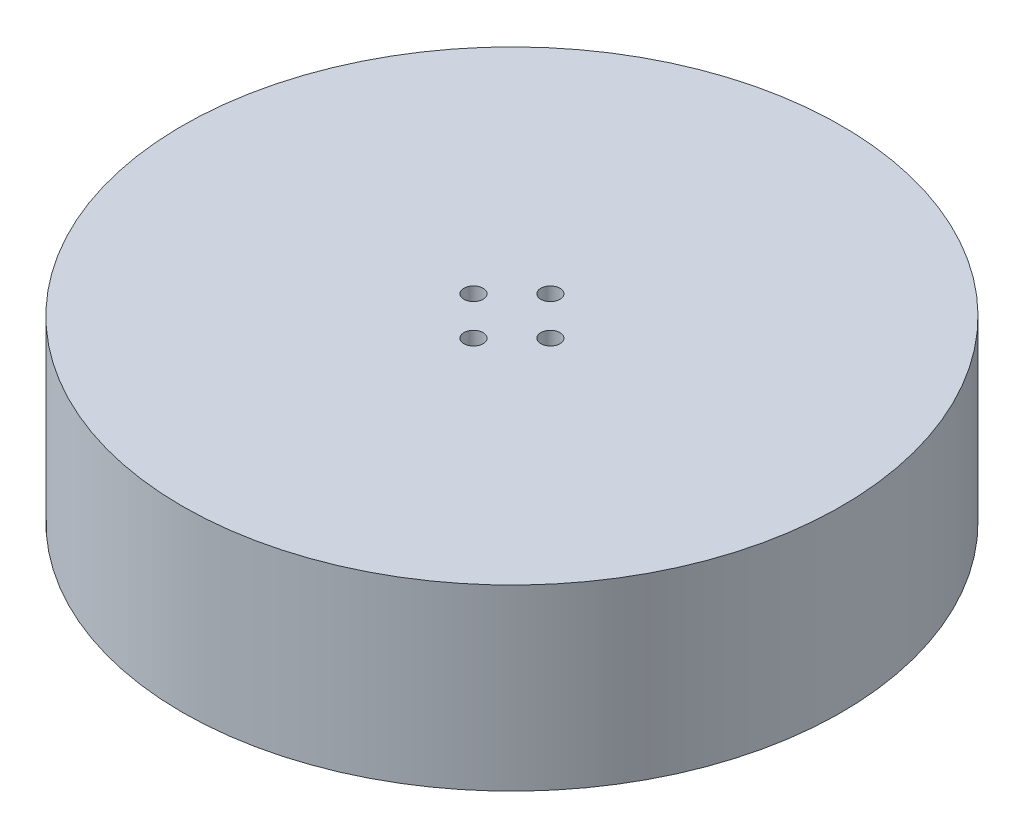
SolidWorks part; units mm, degrees
ref_plane "前视基准面" through (0, 0, 0) normal (0, 0, 1) x (1, 0, 0)
ref_plane "上视基准面" through (0, 0, 0) normal (0, 1, 0) x (1, 0, 0)
ref_plane "右视基准面" through (0, 0, 0) normal (1, 0, 0) x (0, 0, -1)
other "Configuration Table"
sketch "草图1" plane through (0, 0, 0) normal (0, 1, 0) x (1, 0, 0)
  circle A0 centre (0, 0) radius 60
  dimension "D1" = 120
extrude "凸台-拉伸1" add sketch "草图1" along normal blind 32.5
sketch "草图2" plane through (0, 32.5, 0) normal (0, 1, 0) x (1, 0, 0)
  circle A0 centre (0, 0) radius 7 construction
  circle A1 centre (7, 0) radius 1.75
  circle A2 centre (0, -7) radius 1.75
  circle A3 centre (-7, 0) radius 1.75
  circle A4 centre (0, 7) radius 1.75
  dimension "D1" = 3.5
  dimension "D2" = 3.5
  dimension "D3" = 3.5
  dimension "D4" = 3.5
  dimension "D5" = 14
extrude "切除-拉伸1" cut sketch "草图2" against normal blind 10
sketch "草图3" plane through (0, 32.5, 0) normal (0, 1, 0) x (1, 0, 0)
  circle A0 centre (0, 0) radius 35
  dimension "D1" = 70
